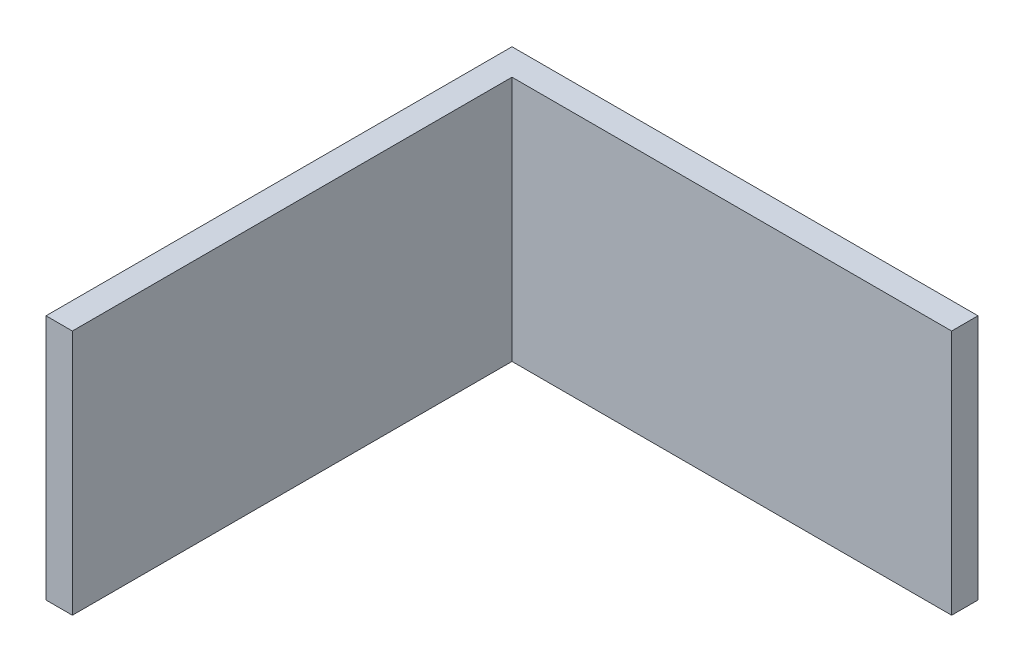
SolidWorks part; units mm, degrees
ref_plane "Front Plane" through (0, 0, 0) normal (0, 0, 1) x (1, 0, 0)
ref_plane "Top Plane" through (0, 0, 0) normal (0, 1, 0) x (1, 0, 0)
ref_plane "Right Plane" through (0, 0, 0) normal (1, 0, 0) x (0, 0, -1)
sketch "Sketch1" plane through (0, 0, 0) normal (0, 0, 1) x (1, 0, 0)
  line L1 (-13.25, -7) -> (13.25, -7)
  line L2 (-13.25, -7) -> (-13.25, 7)
  line L3 (-13.25, 7) -> (13.25, 7)
  line L4 (13.25, -7) -> (13.25, 7)
  line L5 (-13.25, -7) -> (13.25, 7) construction
  line L6 (-13.25, 7) -> (13.25, -7) construction
  point P0 (0, 0)
  dimension "D1" = 14
  dimension "D2" = 26.5
extrude "Boss-Extrude1" add sketch "Sketch1" along normal blind 1.5
sketch "Sketch8" plane through (0, 0, 1.5) normal (0, 0, 1) x (1, 0, 0)
  line L0 (13.25, 7) -> (-13.25, 7) construction
  line L1 (-13.25, -7) -> (-11.75, -7)
  line L2 (-13.25, -7) -> (-13.25, 7)
  line L3 (-13.25, 7) -> (-11.75, 7)
  line L4 (-11.75, -7) -> (-11.75, 7)
  dimension "D1" = 1.5
extrude "Boss-Extrude2" add sketch "Sketch8" along normal blind 25
